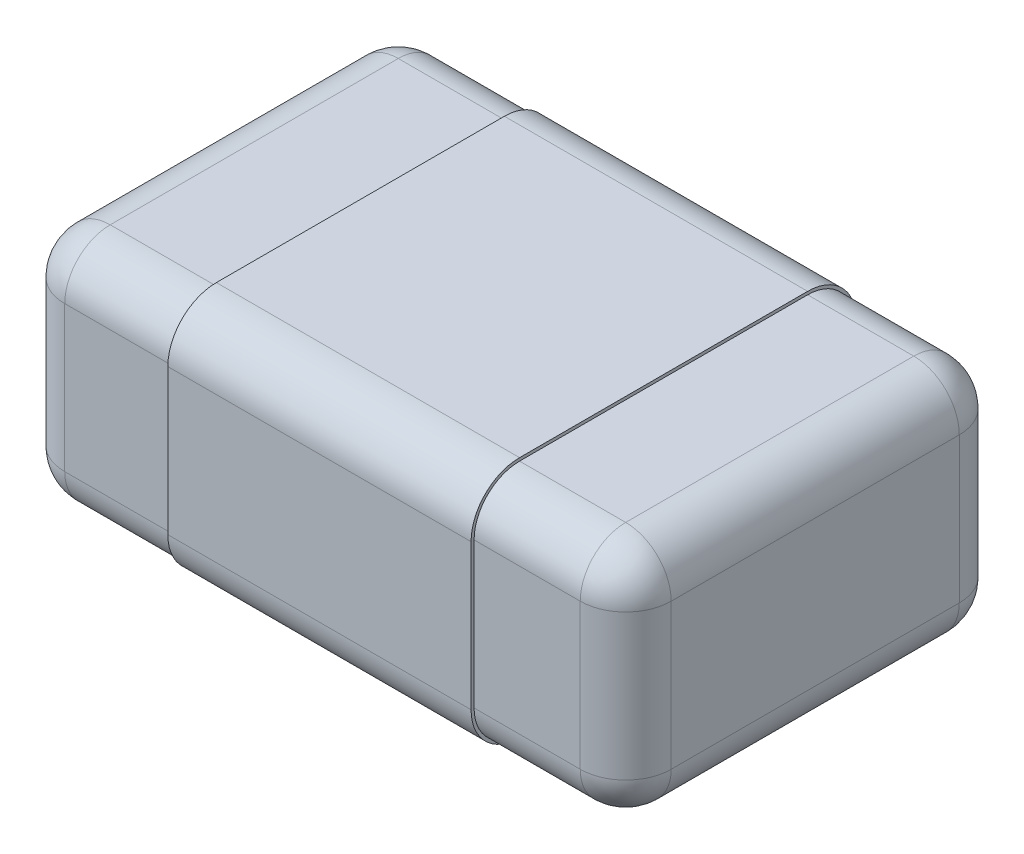
SolidWorks part; units mm, degrees
material "Liga 1060"
ref_plane "Plano frontal" through (0, 0, 0) normal (0, 0, 1) x (1, 0, 0)
ref_plane "Plano superior" through (0, 0, 0) normal (0, 1, 0) x (1, 0, 0)
ref_plane "Plano direito" through (0, 0, 0) normal (1, 0, 0) x (0, 0, -1)
sketch "Esboço1" plane through (0, 0, 0) normal (0, 1, 0) x (1, 0, 0)
  line L0 (-1, -0.625) -> (1, -0.625)
  line L1 (1, -0.625) -> (1, 0.625)
  line L2 (1, 0.625) -> (-1, 0.625)
  line L3 (-1, 0.625) -> (-1, -0.625)
extrude "Ressalto-extrusão1" add sketch "Esboço1" against normal blind 0.78
fillet "Filete1" radius 0.15 12 edges at (0, -0.78, -0.625) (-1, -0.39, -0.625) (1, -0.39, -0.625) (0, 0, -0.625) (-1, -0.78, 0) (1, -0.78, 0) (0, -0.78, 0.625) (-1, 0, 0) (1, 0, 0) (-1, -0.39, 0.625) (1, -0.39, 0.625) (0, 0, 0.625)
sketch "Esboço4" plane through (0, 0, 0) normal (1, 0, 0) x (0, 0, -1)
  line L0 (0.625, -0.63) -> (0.625, -0.15) construction
  line L1 (0.625, -0.63) -> (0.625, -0.15)
  line L2 (0.475, -0.78) -> (-0.475, -0.78) construction
  line L3 (0.475, -0.78) -> (-0.475, -0.78)
  line L4 (0.475, 0) -> (-0.475, 0) construction
  line L5 (-0.625, -0.15) -> (-0.625, -0.63) construction
  line L6 (0.475, 0) -> (-0.475, 0)
  line L7 (-0.625, -0.15) -> (-0.625, -0.63)
  line L8 (0.635, -0.63) -> (0.635, -0.15)
  line L9 (0.475, 0.01) -> (-0.475, 0.01)
  line L10 (-0.635, -0.15) -> (-0.635, -0.63)
  line L11 (0.475, -0.79) -> (-0.475, -0.79)
  arc A5 (0.475, -0.78) -> (0.625, -0.63) centre (0.475, -0.63) ccw construction
  arc A6 (0.475, -0.78) -> (0.625, -0.63) centre (0.475, -0.63) ccw
  arc A7 (-0.475, 0) -> (-0.625, -0.15) centre (-0.475, -0.15) ccw construction
  arc A8 (-0.625, -0.63) -> (-0.475, -0.78) centre (-0.475, -0.63) ccw construction
  arc A9 (-0.475, 0) -> (-0.625, -0.15) centre (-0.475, -0.15) ccw
  arc A10 (-0.625, -0.63) -> (-0.475, -0.78) centre (-0.475, -0.63) ccw
  arc A11 (0.625, -0.15) -> (0.475, 0) centre (0.475, -0.15) ccw construction
  arc A12 (0.625, -0.15) -> (0.475, 0) centre (0.475, -0.15) ccw
  arc A13 (0.635, -0.15) -> (0.475, 0.01) centre (0.475, -0.15) ccw
  arc A14 (-0.475, 0.01) -> (-0.635, -0.15) centre (-0.475, -0.15) ccw
  arc A15 (-0.635, -0.63) -> (-0.475, -0.79) centre (-0.475, -0.63) ccw
  arc A16 (0.475, -0.79) -> (0.635, -0.63) centre (0.475, -0.63) ccw
  dimension "D1" = 0.01
extrude "Ressalto-extrusão4" add sketch "Esboço4" along normal blind 0.5 and the other way blind 0.5
sketch "Esboço2" plane through (0, -0.79, 0) normal (0, -1, 0) x (0, 0, 1)
  line L1 (-0.475, 0.5) -> (0.475, 0.5) construction
  line L2 (-0.475, -0.5) -> (0.475, -0.5) construction
  line L7 (0.2404, -0.5) -> (0.2404, 0.5) construction
  text T0 "<b>103</b>" font "Tahoma" height 0.5
extrude "Ressalto-extrusão5" add sketch "Esboço2" along normal blind 0.02
